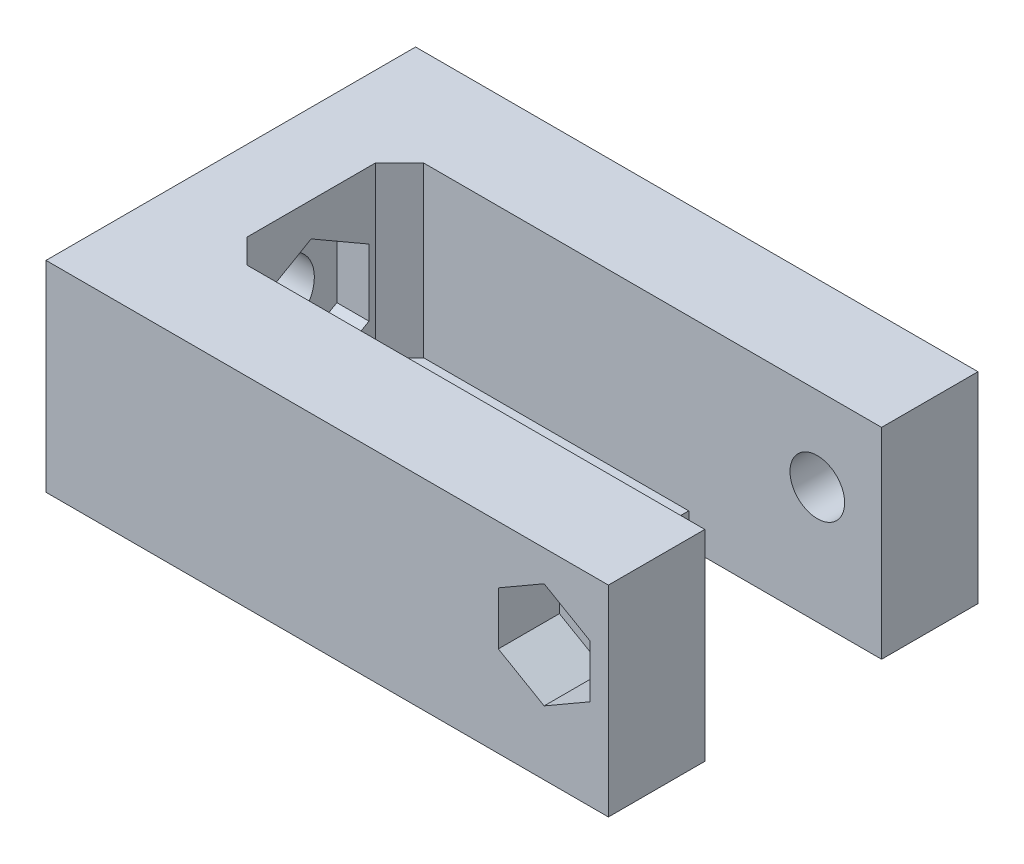
SolidWorks part; units mm, degrees
ref_plane "Front Plane" through (0, 0, 0) normal (0, 0, 1) x (1, 0, 0)
ref_plane "Top Plane" through (0, 0, 0) normal (0, 1, 0) x (1, 0, 0)
ref_plane "Right Plane" through (0, 0, 0) normal (1, 0, 0) x (0, 0, -1)
sketch "Sketch1" plane through (0, 0, 0) normal (1, 0, 0) x (0, 0, -1)
  line L1 (0, 0) -> (23, 0)
  line L2 (0, 0) -> (0, 12.5)
  line L3 (0, 12.5) -> (23, 12.5)
  line L4 (23, 0) -> (23, 12.5)
  dimension "D1" = 23
  dimension "D2" = 12.5
extrude "Boss-Extrude1" add sketch "Sketch1" along normal blind 35
sketch "Sketch2" plane through (35, 0, 0) normal (1, 0, 0) x (0, 0, -1)
  line L0 (11.5, 12.5) -> (11.5, 0) construction
  line L1 (6, 12.5) -> (17, 12.5)
  line L2 (6, 12.5) -> (6, 0)
  line L3 (6, 0) -> (17, 0)
  line L4 (17, 12.5) -> (17, 0)
  line L5 (0, 0) -> (23, 0) construction
  line L8 (23, 12.5) -> (0, 12.5) construction
  line L9 (11.5, 12.5) -> (11.5, 0) construction
  dimension "D1" = 11
extrude "Cut-Extrude1" cut sketch "Sketch2" against normal offset from surface (30 mm away) 5 up to face at (0, 6.25, -11.5)
sketch "Sketch3" plane through (0, 0, -23) normal (0, 0, -1) x (-1, 0, 0)
  line L1 (-35, 0) -> (-35, 12.5) construction
  line L2 (-35, 0) -> (0, 0) construction
  circle A0 centre (-31, 7.28) radius 1.7
  dimension "D3" = 3.4
  dimension "D1" = 7.28
  dimension "D2" = 4
extrude "Cut-Extrude2" cut sketch "Sketch3" against normal through all both and the other way through all
sketch "Sketch4" plane through (0, 0, 0) normal (-1, 0, 0) x (0, 0, 1)
  line L0 (-11.5, 12.5) -> (-11.5, 0) construction
  line L3 (-17, 12.5) -> (-6, 12.5) construction
  line L6 (-6, 0) -> (-17, 0) construction
  circle A0 centre (-11.5, 6.25) radius 2.2
  dimension "D1" = 4.4
  dimension "D2" = 6.25
extrude "Cut-Extrude3" cut sketch "Sketch4" against normal blind 10
sketch "Sketch5" plane through (5, 0, 0) normal (1, 0, 0) x (0, 0, -1)
  line L1 (7.9, 8.3285) -> (7.9, 4.1715)
  line L2 (7.9, 4.1715) -> (11.5, 2.0931)
  line L3 (11.5, 2.0931) -> (15.1, 4.1715)
  line L4 (15.1, 4.1715) -> (15.1, 8.3285)
  line L5 (15.1, 8.3285) -> (11.5, 10.4069)
  line L6 (11.5, 10.4069) -> (7.9, 8.3285)
  circle A0 centre (11.5, 6.25) radius 3.6 construction
  dimension "D1" = 7.2
extrude "Cut-Extrude4" cut sketch "Sketch5" against normal blind 2
sketch "Sketch6" plane through (0, 0, -23) normal (0, 0, -1) x (-1, 0, 0)
  circle A0 centre (-31, 7.28) radius 3.25
  dimension "D1" = 6.5
extrude "Cut-Extrude5" cut sketch "Sketch6" against normal blind 2.5
sketch "Sketch7" plane through (0, 0, 0) normal (0, 0, 1) x (1, 0, 0)
  line L1 (28.15, 8.9254) -> (28.15, 5.6346)
  line L2 (28.15, 5.6346) -> (31, 3.9891)
  line L3 (31, 3.9891) -> (33.85, 5.6346)
  line L4 (33.85, 5.6346) -> (33.85, 8.9254)
  line L5 (33.85, 8.9254) -> (31, 10.5709)
  line L6 (31, 10.5709) -> (28.15, 8.9254)
  circle A0 centre (31, 7.28) radius 2.85 construction
  dimension "D1" = 5.7
extrude "Cut-Extrude6" cut sketch "Sketch7" against normal blind 3.8
sketch "Sketch8" plane through (0, 0, -6) normal (0, 0, -1) x (-1, 0, 0)
  line L0 (-5, 0) -> (-35, 0) construction
  line L1 (-23, 0) -> (-5, 0)
  line L2 (-23, 0) -> (-23, 2)
  line L3 (-23, 2) -> (-5, 2)
  line L4 (-5, 0) -> (-5, 2)
  dimension "D1" = 2
  dimension "D2" = 18
extrude "Boss-Extrude2" add sketch "Sketch8" along normal up to surface (11 mm away) up to face at (29.3, 7.28, -17)
chamfer "Chamfer2" distance 1.5 angle 45 2 edges at (5, 7.25, -6) (5, 7.25, -17)
